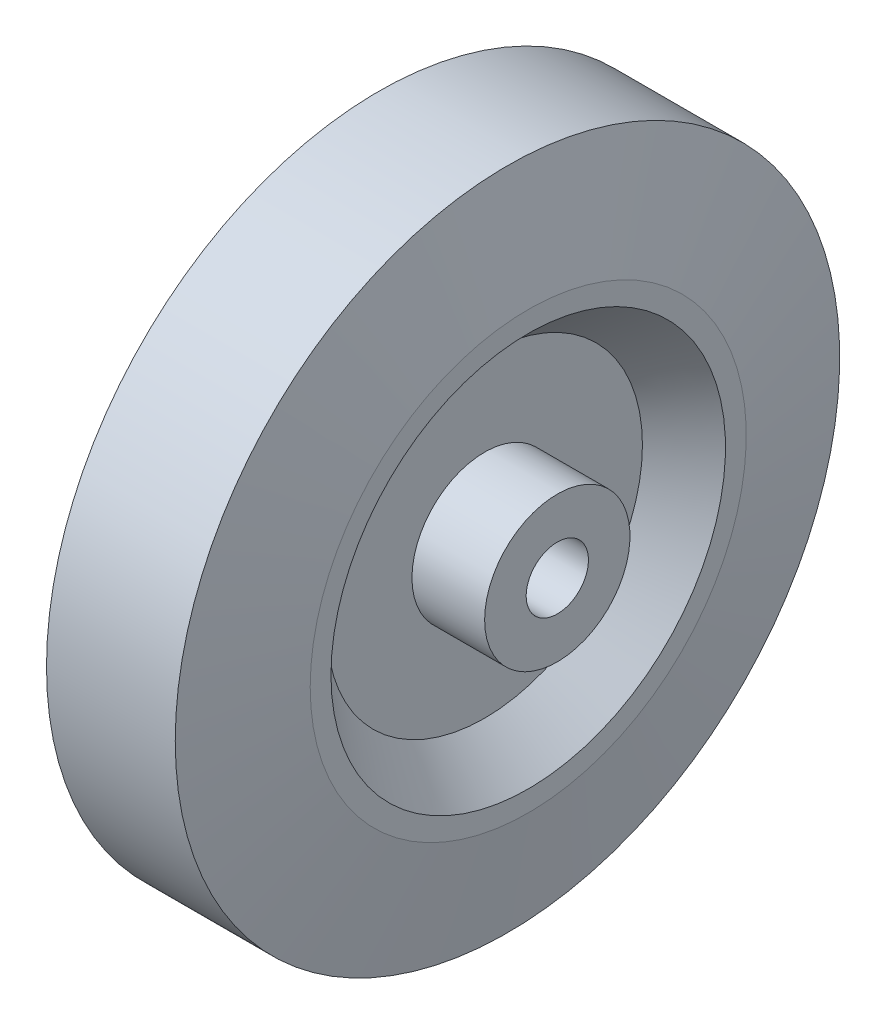
SolidWorks part; units mm, degrees
ref_plane "Alzado" through (0, 0, 0) normal (0, 0, 1) x (1, 0, 0)
ref_plane "Planta" through (0, 0, 0) normal (0, 1, 0) x (1, 0, 0)
ref_plane "Vista lateral" through (0, 0, 0) normal (1, 0, 0) x (0, 0, -1)
sketch "Croquis1" plane through (0, 0, 0) normal (0, 0, 1) x (1, 0, 0)
  line L0 (-30.7882, 0) -> (33.9633, 0) construction
  line L1 (0, -24.6984) -> (0, 82.4535) construction
  line L2 (-15.5, 80) -> (15.5, 80)
  line L3 (15.5, 80) -> (20.5, 52.5)
  line L4 (20.5, 52.5) -> (20.5, 47.5)
  line L5 (20.5, 47.5) -> (10, 38)
  line L6 (10, 38) -> (10, 17.5)
  line L7 (10, 17.5) -> (27.5, 17.5)
  line L8 (27.5, 17.5) -> (27.5, 7.5)
  line L9 (27.5, 7.5) -> (-27.5, 7.5)
  line L10 (-27.5, 17.5) -> (-27.5, 7.5)
  line L11 (-10, 17.5) -> (-27.5, 17.5)
  line L12 (-10, 38) -> (-10, 17.5)
  line L13 (-20.5, 47.5) -> (-10, 38)
  line L14 (-20.5, 52.5) -> (-20.5, 47.5)
  line L15 (-15.5, 80) -> (-20.5, 52.5)
  point P15 (0, 7.5)
  point P21 (0, 80)
  dimension "D1" = 31
  dimension "D2" = 160
  dimension "D3" = 105
  dimension "D4" = 41
  dimension "D5" = 76
  dimension "D6" = 20
  dimension "D7" = 5
  dimension "D8" = 55
  dimension "D9" = 35
  dimension "D10" = 15
revolve "Revolución1" add sketch "Croquis1" angle 360 about L0
